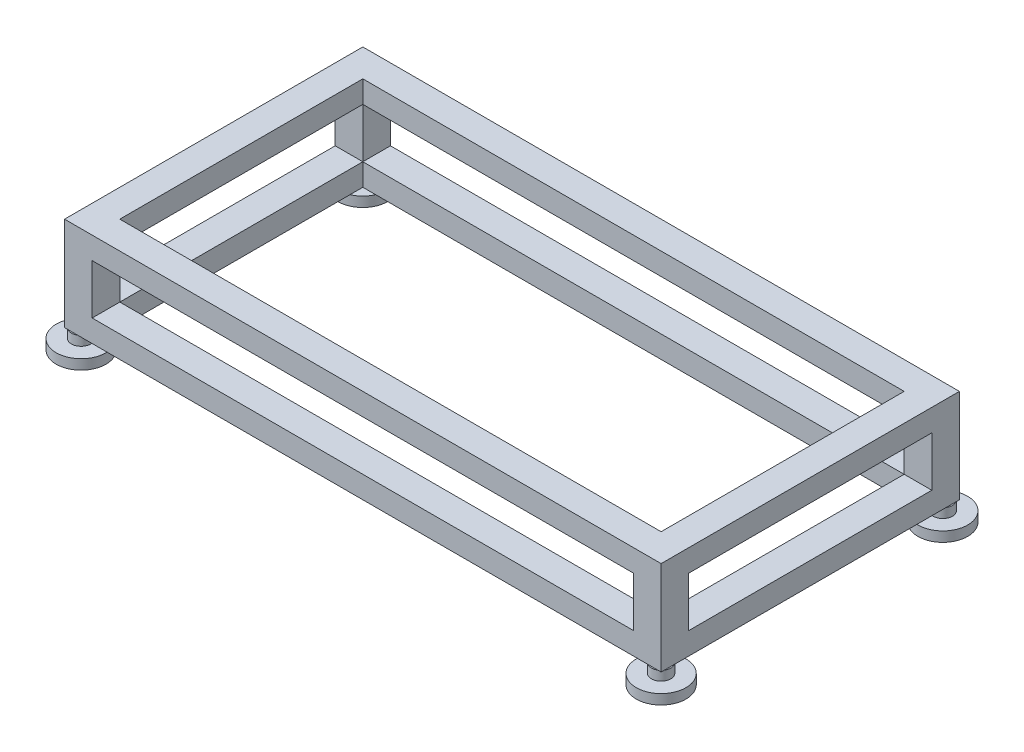
SolidWorks part; units mm, degrees
ref_plane "前视基准面" through (0, 0, 0) normal (0, 0, 1) x (1, 0, 0)
ref_plane "上视基准面" through (0, 0, 0) normal (0, 1, 0) x (1, 0, 0)
ref_plane "右视基准面" through (0, 0, 0) normal (1, 0, 0) x (0, 0, -1)
sketch "草图1" plane through (0, 0, 0) normal (0, 1, 0) x (1, 0, 0)
  line L5 (-480, 270) -> (600, 270)
  line L6 (-480, 270) -> (-480, -270)
  line L7 (-480, -270) -> (600, -270)
  line L8 (600, 270) -> (600, -270)
  point P0 (0, 0)
  dimension "D1" = 600
  dimension "D2" = 1080
  dimension "D3" = 270
  dimension "D4" = 540
extrude "拉伸-薄壁1" add sketch "草图1" against normal blind 170 thin
sketch "草图2" plane through (0, 0, 270) normal (0, 0, 1) x (1, 0, 0)
  line L1 (-430, -40) -> (550, -40)
  line L2 (-430, -40) -> (-430, -130)
  line L3 (-430, -130) -> (550, -130)
  line L4 (550, -40) -> (550, -130)
  line L5 (-430, -40) -> (550, -130) construction
  line L6 (-430, -130) -> (550, -40) construction
  point P0 (60, -85)
  dimension "D1" = 90
  dimension "D2" = 980
extrude "切除-拉伸1" cut sketch "草图2" against normal through all
sketch "草图3" plane through (-480, 0, 0) normal (-1, 0, 0) x (0, 0, 1)
  line L1 (-220, -40) -> (220, -40)
  line L2 (-220, -40) -> (-220, -130)
  line L3 (-220, -130) -> (220, -130)
  line L4 (220, -40) -> (220, -130)
  line L5 (-220, -40) -> (220, -130) construction
  line L6 (-220, -130) -> (220, -40) construction
  point P0 (0, -85)
  dimension "D1" = 90
  dimension "D2" = 440
extrude "切除-拉伸2" cut sketch "草图3" against normal through all
sketch "草图6" plane through (0, 0, 0) normal (0, 1, 0) x (1, 0, 0)
  circle A0 centre (-465, -255) radius 45
  circle A1 centre (-465, 255) radius 45
  circle A2 centre (585, -255) radius 45
  circle A3 centre (585, 255) radius 45
extrude "Four Base Pads" add sketch "草图6" against normal blind 18 from offset 187 separate body
sketch "草图7" plane through (0, 0, 0) normal (0, 1, 0) x (1, 0, 0)
  circle A0 centre (-465, -255) radius 17.5
  circle A1 centre (-465, 255) radius 17.5
  circle A2 centre (585, -255) radius 17.5
  circle A3 centre (585, 255) radius 17.5
extrude "Four Foot Stems" add sketch "草图7" against normal blind 17 from offset 170
